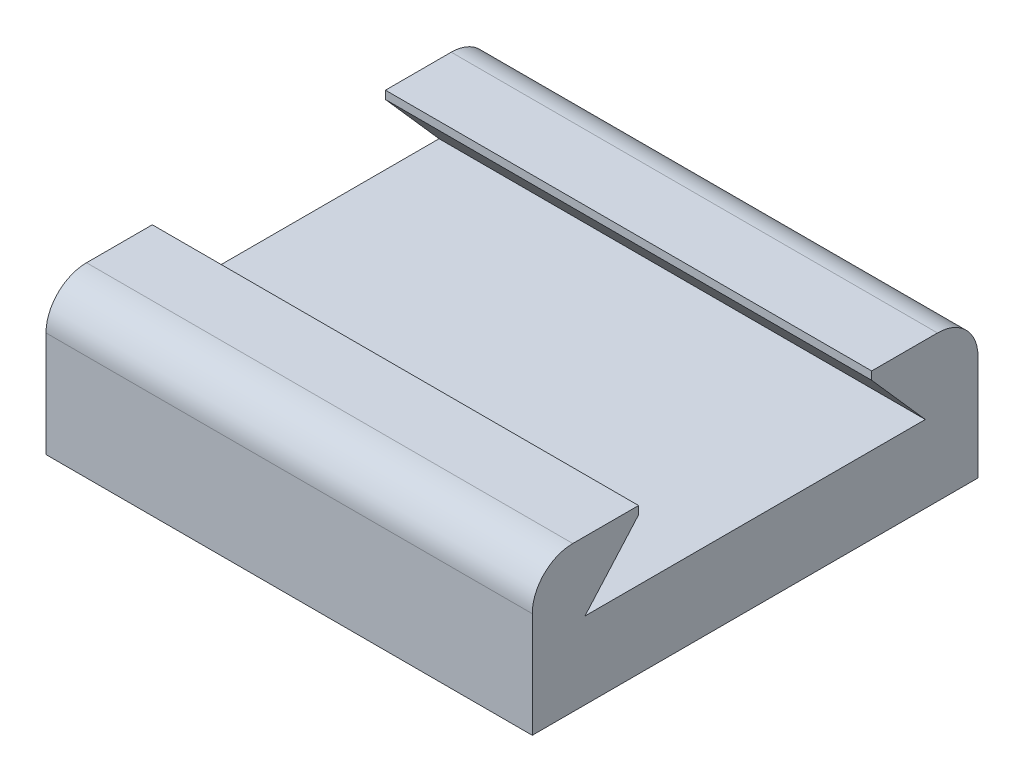
SolidWorks part; units mm, degrees
ref_plane "Front Plane" through (0, 0, 0) normal (0, 0, 1) x (1, 0, 0)
ref_plane "Top Plane" through (0, 0, 0) normal (0, 1, 0) x (1, 0, 0)
ref_plane "Right Plane" through (0, 0, 0) normal (1, 0, 0) x (0, 0, -1)
sketch "Sketch1" plane through (0, 0, 0) normal (0, 1, 0) x (1, 0, 0)
  line L1 (0, 0) -> (12, 0)
  line L2 (0, 0) -> (0, -11)
  line L3 (0, -11) -> (12, -11)
  line L4 (12, 0) -> (12, -11)
  dimension "D1" = 11
  dimension "D2" = 12
extrude "Boss-Extrude1" add sketch "Sketch1" along normal blind 1.6
sketch "Sketch2" plane through (0, 1.6, 0) normal (0, 1, 0) x (1, 0, 0)
  line L1 (0, -11) -> (12, -11)
  line L2 (0, -11) -> (0, 0)
  line L3 (0, 0) -> (12, 0)
  line L4 (12, -11) -> (12, 0)
extrude "Boss-Extrude2" add sketch "Sketch2" along normal blind 2
sketch "Sketch3" plane through (12, 0, 0) normal (1, 0, 0) x (0, 0, -1)
  line L0 (-9.7, 1.9) -> (-8.2, 3.6)
  line L1 (-11, 3.6) -> (0, 3.6) construction
  line L2 (-9.7, 1.9) -> (-1.3, 1.9)
  line L3 (-2.8, 3.6) -> (-1.3, 1.9)
  line L4 (-2.8, 3.6) -> (-8.2, 3.6)
  line L5 (-11, 3.6) -> (-11, 0) construction
  dimension "D1" = 8.4
  dimension "D2" = 5.4
  dimension "D4" = 1.3
  dimension "D3" = 1.7
  dimension "D5" = 2.8
extrude "Cut-Extrude1" cut sketch "Sketch3" against normal through all
sketch "Sketch4" plane through (12, 0, 0) normal (1, 0, 0) x (0, 0, -1)
  line L0 (-8.3765, 3.4) -> (-8.3765, 3.6)
  line L1 (-8.2, 3.6) -> (-9.7, 1.9) construction
  line L2 (-11, 3.6) -> (-8.2, 3.6) construction
  line L3 (-8.3765, 3.4) -> (-8.2, 3.6)
  line L4 (-8.2, 3.6) -> (-8.3765, 3.6)
  line L5 (-2.6235, 3.4) -> (-2.6235, 3.6)
  line L6 (-1.3, 1.9) -> (-2.8, 3.6) construction
  line L7 (-2.8, 3.6) -> (0, 3.6) construction
  line L8 (-2.6235, 3.6) -> (-2.8, 3.6)
  line L9 (-2.8, 3.6) -> (-2.6235, 3.4)
  dimension "D1" = 0.2
  dimension "D2" = 0.2
extrude "Cut-Extrude2" cut sketch "Sketch4" against normal through all
fillet "Fillet1" radius 1 2 edges at (6, 3.6, 0) (6, 3.6, 11)
equation "\"D5@Sketch3\"=(11-5.4)/2"
